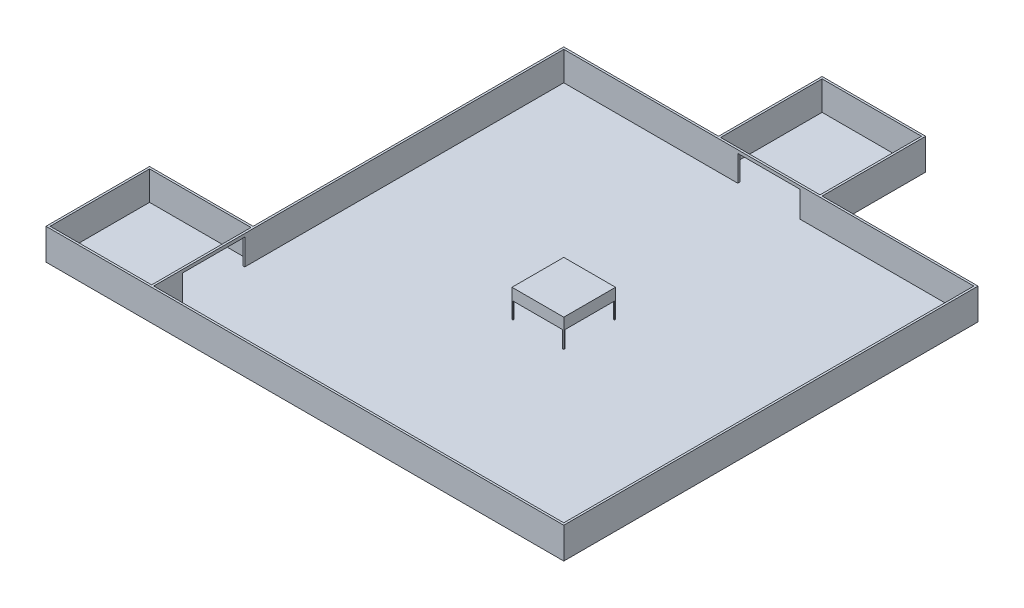
SolidWorks part; units mm, degrees
ref_plane "前视基准面" through (0, 0, 0) normal (0, 0, 1) x (1, 0, 0)
ref_plane "上视基准面" through (0, 0, 0) normal (0, 1, 0) x (1, 0, 0)
ref_plane "右视基准面" through (0, 0, 0) normal (1, 0, 0) x (0, 0, -1)
other "Configuration Table"
sketch "草图1" plane through (0, 0, 0) normal (0, 1, 0) x (1, 0, 0)
  line L0 (0, 0) -> (0, 4000)
  line L1 (0, 4000) -> (4000, 4000)
  line L2 (4000, 4000) -> (4000, 0)
  line L3 (4000, 0) -> (0, 0)
  dimension "D1" = 4000
  dimension "D2" = 4000
extrude "凸台-拉伸1" add sketch "草图1" along normal blind 300 contours L3 L0 L1 L2
sketch "草图2" plane through (0, 300, 0) normal (0, 1, 0) x (1, 0, 0)
  line L0 (20, 3980) -> (3980, 3980)
  line L1 (3980, 3980) -> (3980, 20)
  line L2 (3980, 20) -> (20, 20)
  line L3 (20, 20) -> (20, 3980)
  line L4 (4000, 4000) -> (4000, 0) construction
  line L5 (0, 4000) -> (4000, 4000) construction
  line L6 (0, 0) -> (0, 4000) construction
  line L7 (4000, 0) -> (0, 0) construction
  dimension "D1" = 20
  dimension "D2" = 20
  dimension "D3" = 20
  dimension "D4" = 20
extrude "切除-拉伸1" cut sketch "草图2" against normal blind 280
sketch "草图3" plane through (0, 0, -4000) normal (0, 0, -1) x (-1, 0, 0)
  line L0 (-2000, 643.7534) -> (-2000, -168.5082) construction
  line L1 (-1700, 270) -> (-2300, 270)
  line L2 (-2300, 270) -> (-2300, 20)
  line L3 (-2300, 20) -> (-1700, 20)
  line L4 (-1700, 270) -> (-1700, 20)
  line L5 (0, 0) -> (-4000, 0) construction
  line L6 (0, 300) -> (0, 0) construction
  point P7 (-2000, 20)
  point P8 (-2000, 270)
  dimension "D1" = 600
  dimension "D2" = 250
  dimension "D3" = 20
  dimension "D4" = 1700
extrude "切除-拉伸2" cut sketch "草图3" against normal blind 20
sketch "草图5" plane through (0, 0, 0) normal (-1, 0, 0) x (0, 0, 1)
  line L0 (-600, 365.7553) -> (-600, -137.7591) construction
  line L1 (-300, 20) -> (-900, 20)
  line L2 (-900, 20) -> (-900, 270)
  line L3 (-900, 270) -> (-300, 270)
  line L4 (-300, 20) -> (-300, 270)
  line L5 (0, 0) -> (-4000, 0) construction
  line L6 (0, 300) -> (0, 0) construction
  point P2 (-600, 270)
  point P8 (-600, 20)
  dimension "D1" = 20
  dimension "D2" = 250
  dimension "D3" = 600
  dimension "D4" = 300
extrude "切除-拉伸3" cut sketch "草图5" against normal blind 20
sketch "草图6" plane through (0, 20, 0) normal (0, 1, 0) x (1, 0, 0)
  line L0 (4417.4375, 2000) -> (-502.2256, 2000) construction
  line L1 (2000, 4803.7985) -> (2000, -159.9476) construction
  line L2 (2250, 2250) -> (2250, 1750)
  line L3 (2250, 1750) -> (1750, 1750)
  line L4 (1750, 2250) -> (1750, 1750)
  line L5 (2250, 2250) -> (1750, 2250)
  line L6 (20, 20) -> (3980, 20) construction
  line L7 (3980, 3980) -> (20, 3980) construction
  line L8 (20, 3980) -> (20, 900) construction
  line L9 (3980, 20) -> (3980, 3980) construction
  point P9 (2000, 1750)
  point P10 (1750, 2000)
  point P11 (2250, 2000)
  dimension "D1" = 1730
  dimension "D2" = 1730
  dimension "D3" = 1730
  dimension "D4" = 1730
extrude "凸台-拉伸2" add sketch "草图6" along normal blind 270
sketch "草图8" plane through (0, 0, -1750) normal (0, 0, 1) x (1, 0, 0)
  line L0 (2000, -336.1411) -> (2000, 576.6479) construction
  line L2 (4000, 0) -> (0, 0) construction
  line L8 (1760, 180) -> (1760, 20)
  line L9 (1760, 20) -> (2240, 20)
  line L10 (1760, 180) -> (2240, 180)
  line L11 (2240, 180) -> (2240, 20)
  point P8 (2000, 180)
  point P9 (2000, 0)
  point P10 (2000, 180)
  point P12 (2000, 20)
  dimension "D1" = 20
  dimension "D2" = 480
  dimension "D3" = 160
extrude "切除-拉伸4" cut sketch "草图8" against normal blind 500
sketch "草图11" plane through (1750, 0, 0) normal (-1, 0, 0) x (0, 0, 1)
  line L0 (-2000, 620.6935) -> (-2000, -207.6525) construction
  line L1 (-1760, 20) -> (-2240, 20)
  line L2 (-2240, 20) -> (-2240, 180)
  line L3 (-2240, 180) -> (-1760, 180)
  line L4 (-1760, 20) -> (-1760, 180)
  line L5 (0, 0) -> (-4000, 0) construction
  line L7 (-4000, 300) -> (-4000, 0) construction
  point P7 (-2000, 20)
  point P8 (-2000, 180)
  dimension "D1" = 480
  dimension "D2" = 20
  dimension "D3" = 1760
  dimension "D4" = 160
extrude "切除-拉伸5" cut sketch "草图11" against normal blind 500
sketch "草图12" plane through (0, 20, 0) normal (0, 1, 0) x (1, 0, 0)
  line L0 (0, 1000) -> (-1000, 1000)
  line L1 (0, 0) -> (0, 4000) construction
  line L2 (-1000, 1000) -> (-1000, 0)
  line L3 (-1000, 0) -> (0, 0)
  line L4 (0, 1000) -> (0, 0)
  line L5 (2494.4232, 5000) -> (1494.4232, 5000)
  line L6 (1494.4232, 5000) -> (1494.4232, 4000)
  line L7 (0, 4000) -> (4000, 4000) construction
  line L8 (1494.4232, 4000) -> (2494.4232, 4000)
  line L9 (2494.4232, 4000) -> (2494.4232, 5000)
  line L10 (1994.4232, 5277.9673) -> (1994.4232, -148.4943) construction
  point P15 (2494.4232, 4500)
  dimension "D1" = 1000
  dimension "D2" = 1000
  dimension "D3" = 500
  dimension "D4" = 500
  dimension "D5" = 1000
extrude "凸台-拉伸3" add sketch "草图12" against normal blind 20 and the other way blind 280
sketch "草图13" plane through (0, 300, 0) normal (0, 1, 0) x (1, 0, 0)
  line L0 (0, 980) -> (-980, 980)
  line L1 (-980, 980) -> (-980, 20)
  line L2 (-980, 20) -> (0, 20)
  line L3 (0, 20) -> (0, 980)
  line L4 (0, 1000) -> (-1000, 1000) construction
  line L5 (-1000, 1000) -> (-1000, 0) construction
  line L6 (4000, 0) -> (-1000, 0) construction
  line L7 (20, 3980) -> (20, 20) construction
  line L9 (2474.4232, 4980) -> (1514.4232, 4980)
  line L12 (2494.4232, 5000) -> (1494.4232, 5000) construction
  line L16 (2474.4232, 4980) -> (2474.4232, 4000)
  line L17 (2474.4232, 4000) -> (1514.4232, 4000)
  line L18 (1514.4232, 4000) -> (1514.4232, 4980)
  line L19 (3980, 3980) -> (20, 3980) construction
  line L20 (2494.4232, 4000) -> (2494.4232, 5000) construction
  line L21 (1494.4232, 5000) -> (1494.4232, 4000) construction
  dimension "D1" = 20
  dimension "D2" = 20
  dimension "D3" = 20
  dimension "D4" = 20
  dimension "D5" = 20
  dimension "D6" = 20
  dimension "D7" = 20
  dimension "D8" = 20
extrude "切除-拉伸6" cut sketch "草图13" against normal blind 280
